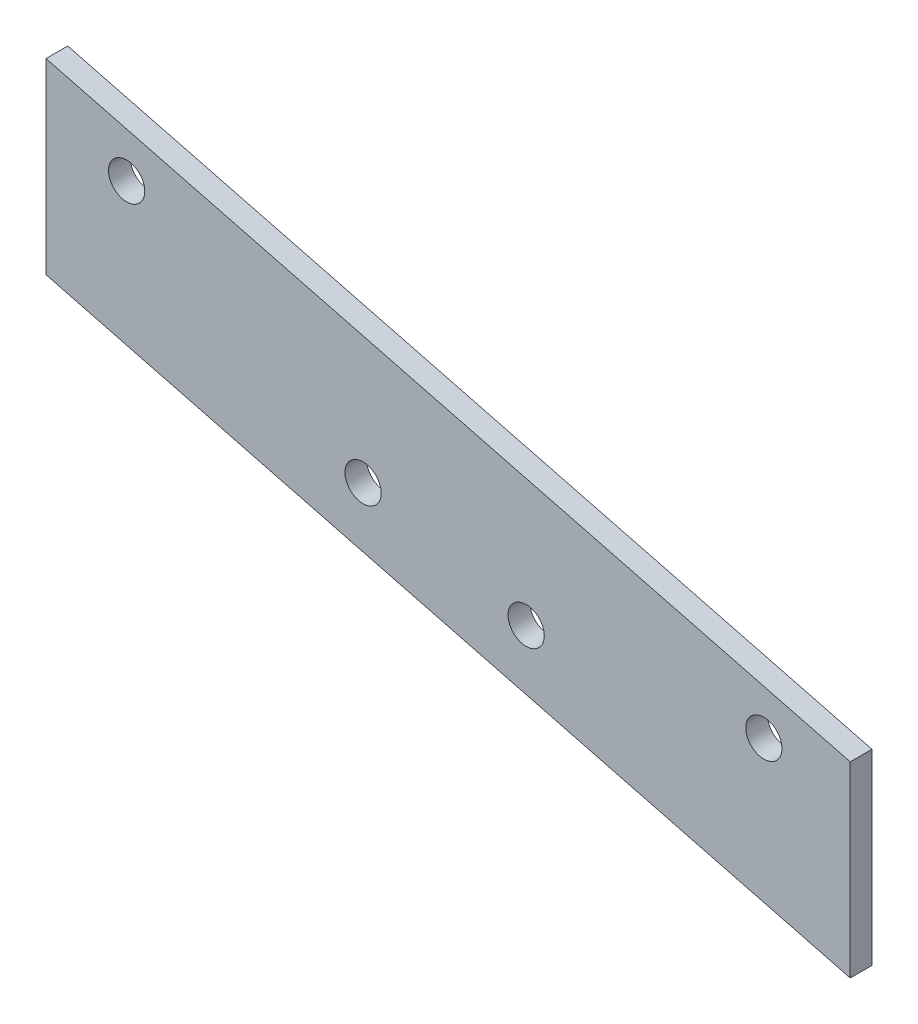
SolidWorks part; units mm, degrees
material "AISI 4340 Aço, normalizado"
ref_plane "Plano frontal" through (0, 0, 0) normal (0, 0, 1) x (1, 0, 0)
ref_plane "Plano superior" through (0, 0, 0) normal (0, 1, 0) x (1, 0, 0)
ref_plane "Plano direito" through (0, 0, 0) normal (1, 0, 0) x (0, 0, -1)
sketch "Esboço1" plane through (0, 0, 0) normal (0, 0, 1) x (1, 0, 0)
  line L7 (0, 0) -> (0, 25.8144)
  line L8 (0, 25.8144) -> (110.8975, -2.7212)
  line L9 (110.8975, -2.7212) -> (110.8975, -28.5355)
  line L10 (110.8975, -28.5355) -> (0, 0)
  dimension "D1" = 104.43
  dimension "D2" = 25
  dimension "D4" = 114.51
extrude "Ressalto-extrusão1" add sketch "Esboço1" along normal blind 3
hole_wizard "Broca de rosquear para tarraxa de M61" positions "Esboço4" profile "Esboço5" hole size "M6" standard "ISO" end condition through all
sketch "Esboço4" plane through (0, 0, 3) normal (0, 0, 1) x (1, 0, 0)
  line L0 (11.1178, 16.7581) -> (43.7208, -2.9894)
  line L1 (43.7208, -2.9894) -> (66.2083, -8.7758)
  line L2 (66.2083, -8.7758) -> (98.9856, -5.8515)
  line L3 (98.9856, -5.8515) -> (11.1178, 16.7581)
  line L5 (110.8975, -2.7212) -> (0, 25.8144) construction
  line L6 (0, 0) -> (110.8975, -28.5355) construction
  line L7 (43.7208, -2.9894) -> (0, 8.2606)
  line L8 (0, 25.8144) -> (0, 0) construction
  line L10 (66.2083, -8.7758) -> (110.8975, -20.275)
  line L11 (110.8975, -28.5355) -> (110.8975, -2.7212) construction
  line L14 (11.1178, 16.7581) -> (0, 19.6189)
  line L16 (98.9856, -5.8515) -> (110.8975, -8.9166)
  point P0 (11.1178, 16.7581)
  point P2 (43.7208, -2.9894)
  point P4 (66.2083, -8.7758)
  point P6 (98.9856, -5.8515)
  dimension "D1" = 11.48
  dimension "D2" = 90.73
  dimension "D3" = 17
  dimension "D4" = 6
  dimension "D5" = 23.22
  dimension "D6" = 45.145
sketch "Esboço5" plane through (11.1178, 16.7581, 3) normal (1, 0, 0) x (0, -1, 0)
  line L0 (0, 0) -> (0, 3)
  line L1 (0, 3) -> (2.5, 3)
  line L2 (2.5, 3) -> (2.5, 0)
  line L5 (2.5, 0) -> (0, 0)
  line L11 (0, -6.35) -> (0, 107.95) construction
  dimension "Thru Hole Dia." = 5
  dimension "Thru Hole Depth" = 3
